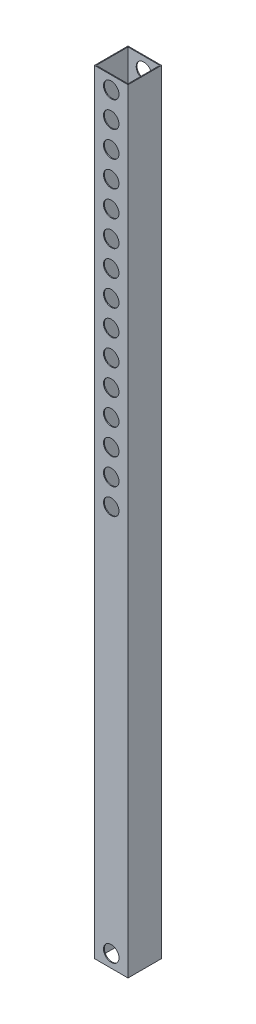
SolidWorks part; units mm, degrees
ref_plane "Alzado" through (0, 0, 0) normal (0, 0, 1) x (1, 0, 0)
ref_plane "Planta" through (0, 0, 0) normal (0, 1, 0) x (1, 0, 0)
ref_plane "Vista lateral" through (0, 0, 0) normal (1, 0, 0) x (0, 0, -1)
sketch "Croquis1" plane through (0, 0, 0) normal (0, 1, 0) x (1, 0, 0)
  line L1 (-6.5, 6.5) -> (6.5, 6.5)
  line L2 (-6.5, 6.5) -> (-6.5, -6.5)
  line L3 (-6.5, -6.5) -> (6.5, -6.5)
  line L4 (6.5, 6.5) -> (6.5, -6.5)
  line L5 (-6.5, 6.5) -> (6.5, -6.5) construction
  line L6 (-6.5, -6.5) -> (6.5, 6.5) construction
  point P0 (0, 0)
  dimension "D1" = 13
  dimension "D2" = 13
extrude "Saliente-Extruir1" add sketch "Croquis1" along normal blind 300
sketch "Croquis2" plane through (0, 300, 0) normal (0, 1, 0) x (1, 0, 0)
  line L0 (-6.5, 6.5) -> (-6.5, -6.5) construction
  line L1 (-6.183, 6.183) -> (6.183, 6.183)
  line L2 (-6.183, 6.183) -> (-6.183, -6.183)
  line L3 (-6.183, -6.183) -> (6.183, -6.183)
  line L4 (6.183, 6.183) -> (6.183, -6.183)
  line L5 (-6.183, 6.183) -> (6.183, -6.183) construction
  line L6 (-6.183, -6.183) -> (6.183, 6.183) construction
  line L7 (6.5, 6.5) -> (-6.5, 6.5) construction
  point P0 (0, 0)
  dimension "D1" = 0.317
  dimension "D2" = 0.317
extrude "Cortar-Extruir1" cut sketch "Croquis2" against normal blind 500
sketch "Croquis3" plane through (0, 0, 6.5) normal (0, 0, 1) x (1, 0, 0)
  line L0 (-6.5, 10) -> (6.5, 10) construction
  line L1 (-6.5, 300) -> (-6.5, 0) construction
  line L2 (6.5, 300) -> (6.5, 0) construction
  line L3 (-6.5, 0) -> (6.5, 0) construction
  line L4 (0, 0) -> (0, 10) construction
  line L5 (-6.5, 5) -> (6.5, 5) construction
  circle A0 centre (0, 5) radius 3
  dimension "D3" = 6
  dimension "D1" = 10
  dimension "D2" = 5
extrude "Cortar-Extruir2" cut sketch "Croquis3" against normal blind 500
sketch "Croquis4" plane through (0, 0, 6.5) normal (0, 0, 1) x (1, 0, 0)
  line L0 (6.5, 290) -> (-6.5, 290) construction
  line L1 (6.5, 300) -> (6.5, 0) construction
  line L2 (-6.5, 300) -> (-6.5, 0) construction
  line L3 (6.5, 295) -> (-6.5, 295) construction
  line L4 (6.5, 300) -> (-6.5, 300) construction
  line L5 (0, 300) -> (0, 290) construction
  circle A0 centre (0, 295) radius 3
  circle A1 centre (0, 285) radius 3
  circle A2 centre (0, 275) radius 3
  circle A3 centre (0, 265) radius 3
  circle A4 centre (0, 255) radius 3
  circle A5 centre (0, 245) radius 3
  circle A6 centre (0, 235) radius 3
  circle A7 centre (0, 225) radius 3
  circle A8 centre (0, 215) radius 3
  circle A9 centre (0, 205) radius 3
  circle A10 centre (0, 195) radius 3
  circle A11 centre (0, 185) radius 3
  circle A12 centre (0, 175) radius 3
  circle A13 centre (0, 165) radius 3
  circle A14 centre (0, 155) radius 3
  dimension "D3" = 6
  dimension "D1" = 10
  dimension "D2" = 5
  dimension "D4" = 15
extrude "Cortar-Extruir3" cut sketch "Croquis4" against normal blind 500
